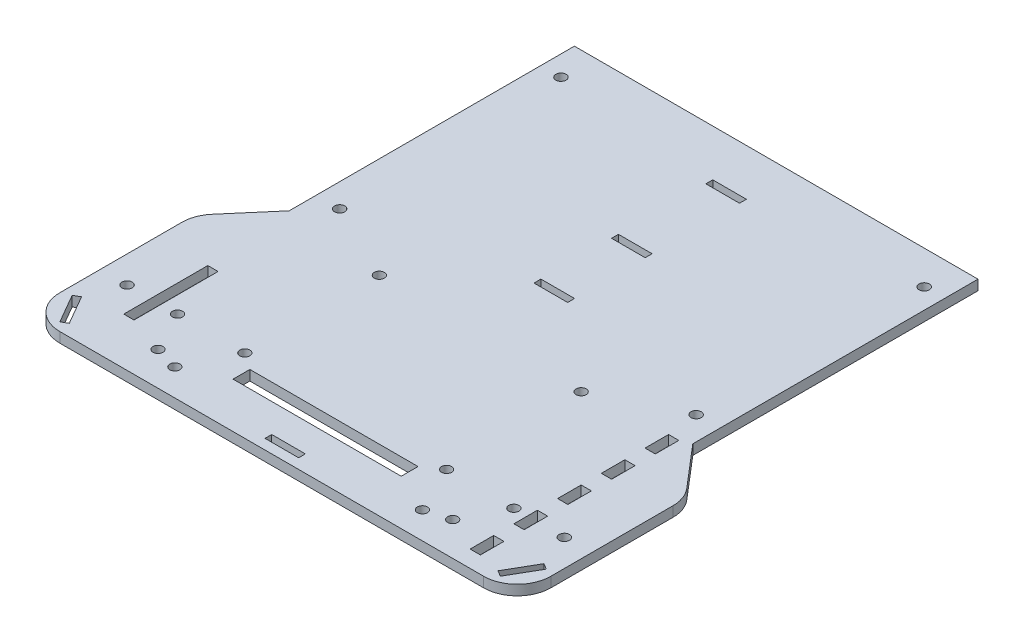
SolidWorks part; units mm, degrees
material "Perspex (TM) GS Acrylic Cast Sheet"
ref_plane "Front Plane" through (0, 0, 0) normal (0, 0, 1) x (1, 0, 0)
ref_plane "Top Plane" through (0, 0, 0) normal (0, 1, 0) x (1, 0, 0)
ref_plane "Right Plane" through (0, 0, 0) normal (1, 0, 0) x (0, 0, -1)
sketch "Sketch1" plane through (0, 0, 0) normal (0, 1, 0) x (1, 0, 0)
  line L0 (-73, -25) -> (-60, -9.8013)
  line L1 (60, -75) -> (-60, -75)
  line L2 (60, -9.8013) -> (60, 75)
  line L3 (60, 75) -> (-60, 75)
  line L4 (-60, -9.8013) -> (-60, 75)
  line L5 (60, -75) -> (-60, 75) construction
  line L6 (60, 75) -> (-60, -75) construction
  line L7 (0, 0) -> (0, -75) construction
  line L9 (-60, -75) -> (-73, -75)
  line L10 (-73, -25) -> (-73, -75)
  line L11 (60, -75) -> (73, -75)
  line L12 (73, -25) -> (73, -75)
  line L13 (73, -25) -> (60, -9.8013)
  point P0 (0, 0)
  dimension "D1" = 150
  dimension "D2" = 120
  dimension "D3" = 50
  dimension "D4" = 13
  dimension "D5" = 20
extrude "Boss-Extrude1" add sketch "Sketch1" along normal blind 3
sketch "Sketch2" plane through (0, 3, 0) normal (0, 1, 0) x (1, 0, 0)
  line L0 (0, 0) -> (0, 75) construction
  line L1 (60, 75) -> (-60, 75) construction
  line L2 (-60, 75) -> (-60, -9.8013) construction
  circle A0 centre (-53, -1.81) radius 1.525
  circle A1 centre (-54, 65) radius 1.525
  circle A2 centre (53, -1.81) radius 1.525
  circle A3 centre (54, 65) radius 1.525
  dimension "D1" = 10
  dimension "D2" = 3.05
  dimension "D3" = 6
  dimension "D4" = 3.05
  dimension "D5" = 7
  dimension "D6" = 66.81
extrude "Cut-Extrude1" cut sketch "Sketch2" against normal through all
sketch "Sketch3" plane through (0, 3, 0) normal (0, 1, 0) x (1, 0, 0)
  line L0 (-5, 33.09) -> (5, 33.09)
  line L1 (-5, 10.04) -> (5, 10.04)
  line L2 (-5, 10.04) -> (-5, 7.99)
  line L3 (-5, 7.99) -> (5, 7.99)
  line L4 (5, 10.04) -> (5, 7.99)
  line L5 (-5, 10.04) -> (5, 7.99) construction
  line L6 (-5, 7.99) -> (5, 10.04) construction
  line L7 (-5, 33.09) -> (-5, 31.04)
  line L8 (-5, 31.04) -> (5, 31.04)
  line L9 (5, 33.09) -> (5, 31.04)
  line L11 (-5, 61.14) -> (5, 61.14)
  line L12 (-5, 61.14) -> (-5, 59.09)
  line L13 (-5, 59.09) -> (5, 59.09)
  line L14 (-5, 56.14) -> (5, 56.14) [skipped]
  line L15 (-5, 56.14) -> (-5, 54.09) [skipped]
  line L16 (-5, 54.09) -> (5, 54.09) [skipped]
  line L17 (5, 56.14) -> (5, 54.09) [skipped]
  line L18 (5, 61.14) -> (5, 59.09)
  line L19 (-5, 61.14) -> (5, 59.09) construction
  line L20 (-5, 59.09) -> (5, 61.14) construction
  circle A0 centre (-53, -1.81) radius 1.525 construction
  point P0 (0, 9.015)
  point P8 (0, 60.115)
  dimension "D2" = 9.8
  dimension "D1" = 2.05
  dimension "D3" = 10
  dimension "D4" = 0
  dimension "D6" = 2.05
  dimension "D7" = 10
  dimension "D8" = 0
  dimension "D9" = 26
  dimension "D10" = 21
  dimension "D5" = 3
extrude "Cut-Extrude2" cut sketch "Sketch3" against normal through all
sketch "Sketch4" plane through (0, 3, 0) normal (0, 1, 0) x (1, 0, 0)
  line L0 (-73, -75) -> (73, -75) construction
  line L1 (-60, 75) -> (-60, -9.8013) construction
  line L2 (0, 0) -> (0, -75) construction
  line L4 (-73, -75) -> (73, -75) construction
  circle A1 centre (-50, -53) radius 1.5
  circle A2 centre (-43.8153, -65) radius 1.5
  circle A3 centre (43.8153, -65) radius 1.5
  circle A4 centre (50, -53) radius 1.5
  dimension "D1" = 3
  dimension "D2" = 3
  dimension "D4" = 10
  dimension "D5" = 13.5
  dimension "D6" = 10
  dimension "D3" = 22
extrude "Cut-Extrude3" cut sketch "Sketch4" against normal blind 3
sketch "Sketch5" plane through (0, 3, 0) normal (0, 1, 0) x (1, 0, 0)
  line L0 (0, 0) -> (0, -75) construction
  line L1 (-73, -75) -> (73, -75) construction
  line L2 (25, -61.5) -> (-25, -61.5)
  line L3 (25, -61.5) -> (25, -56.5)
  line L4 (25, -56.5) -> (-25, -56.5)
  line L5 (-25, -61.5) -> (-25, -56.5)
  line L6 (25, -61.5) -> (-25, -56.5) construction
  line L7 (-73, -75) -> (73, -75) construction
  line L8 (25, -56.5) -> (-25, -61.5) construction
  line L9 (-73, -25) -> (-73, -75) construction
  circle A0 centre (-36.8, -67) radius 1.5
  circle A1 centre (36.8, -67) radius 1.5
  circle A2 centre (-65, -53) radius 1.525
  circle A3 centre (65, -53) radius 1.525
  point P0 (0, -59)
  dimension "D3" = 3
  dimension "D4" = 5.5
  dimension "D5" = 8
  dimension "D7" = 3.05
  dimension "D9" = 8
  dimension "D1" = 5
  dimension "D2" = 50
  dimension "D6" = 36.8
  dimension "D8" = 22
extrude "Cut-Extrude4" cut sketch "Sketch5" against normal blind 3
sketch "Sketch6" plane through (0, 3, 0) normal (0, 1, 0) x (1, 0, 0)
  line L5 (25, -61.5) -> (25, -56.5) construction
  line L11 (-73, -75) -> (73, -75) construction
  line L12 (57.05, -50) -> (57.05, -57)
  line L24 (54, -63) -> (54, -70)
  line L25 (54, -63) -> (57.05, -63)
  line L26 (57.05, -63) -> (57.05, -70)
  line L27 (54, -70) -> (57.05, -70)
  line L28 (54, -50) -> (57.05, -50)
  line L29 (54, -50) -> (54, -57)
  line L30 (54, -57) -> (57.05, -57)
  line L31 (57.05, -37) -> (57.05, -44)
  line L32 (54, -37) -> (57.05, -37)
  line L33 (54, -37) -> (54, -44)
  line L34 (54, -44) -> (57.05, -44)
  line L35 (57.05, -24) -> (57.05, -31)
  line L36 (54, -24) -> (57.05, -24)
  line L37 (54, -24) -> (54, -31)
  line L38 (54, -31) -> (57.05, -31)
  line L39 (57.05, -11) -> (57.05, -18)
  line L40 (54, -11) -> (57.05, -11)
  line L41 (54, -11) -> (54, -18)
  line L42 (54, -18) -> (57.05, -18)
  dimension "D1" = 29
  dimension "D2" = 3.05
  dimension "D3" = 5
  dimension "D4" = 7
  dimension "D5" = 5
  dimension "D6" = 6
extrude "Cut-Extrude5" cut sketch "Sketch6" against normal blind 10
sketch "Sketch7" plane through (0, 3, 0) normal (0, 1, 0) x (1, 0, 0)
  line L0 (-73, -25) -> (-73, -75) construction
  line L1 (54, -40.5) -> (-47.7588, -40.5) construction
  line L2 (-73, -75) -> (73, -75) construction
  line L3 (5, -72) -> (-5, -72)
  line L8 (0, -75) -> (0, -22.2641) construction
  line L13 (5, -72) -> (5, -70)
  line L14 (5, -70) -> (-5, -70)
  line L15 (-5, -72) -> (-5, -70)
  line L20 (5, -72) -> (-5, -70) construction
  line L25 (5, -70) -> (-5, -72) construction
  line L27 (54, -37) -> (54, -44) construction
  line L28 (-58, -61) -> (-54.95, -61)
  line L29 (-58, -61) -> (-58, -36)
  line L30 (-58, -36) -> (-54.95, -36)
  line L31 (-54.95, -61) -> (-54.95, -36)
  line L32 (-58, -61) -> (-54.95, -36) construction
  line L33 (-58, -36) -> (-54.95, -61) construction
  point P10 (0, -71)
  point P18 (-56.475, -48.5)
  dimension "D2" = 2
  dimension "D3" = 25
  dimension "D7" = 3
  dimension "D10" = 15
  dimension "D8" = 3.05
  dimension "D4" = 10
  dimension "D9" = 14
extrude "Cut-Extrude6" cut sketch "Sketch7" against normal blind 10
fillet "Fillet3" radius 10 4 edges at (-73, 1.5, 25) (73, 1.5, 25) (73, 1.5, 75) (-73, 1.5, 75)
sketch "Sketch8" plane through (0, 3, 0) normal (0, 1, 0) x (1, 0, 0)
  line L5 (70.5, -63.8397) -> (65.5, -72.5)
  line L6 (65.5, -72.5) -> (63.7246, -71.475)
  line L8 (-63, -75) -> (63, -75) construction
  line L9 (0, -75) -> (0, -22.4512) construction
  line L14 (63.7246, -71.475) -> (68.7246, -62.8147)
  line L15 (68.7246, -62.8147) -> (70.5, -63.8397)
  line L17 (-68.7246, -62.8147) -> (-70.5, -63.8397)
  line L18 (-63.7246, -71.475) -> (-68.7246, -62.8147)
  line L19 (-65.5, -72.5) -> (-63.7246, -71.475)
  line L20 (-70.5, -63.8397) -> (-65.5, -72.5)
  line L21 (73, -65) -> (73, -28.6933) construction
  dimension "D1" = 2.05
  dimension "D2" = 10
  dimension "D3" = 60
  dimension "D4" = 2.5
  dimension "D5" = 2.5
extrude "Cut-Extrude7" cut sketch "Sketch8" against normal blind 10
sketch "Sketch9" plane through (0, 3, 0) normal (0, 1, 0) x (1, 0, 0)
  line L0 (0, 0) -> (0, -75) construction
  line L1 (-73, -33) -> (73, -33) construction
  line L2 (-63, -75) -> (63, -75) construction
  line L3 (-73, -28.6933) -> (-73, -65) construction
  line L4 (73, -65) -> (73, -28.6933) construction
  circle A0 centre (-30, -13) radius 1.5
  circle A2 centre (30, -13) radius 1.5
  circle A3 centre (30, -53) radius 1.5
  circle A4 centre (-30, -53) radius 1.5
  dimension "D2" = 3
  dimension "D1" = 20
  dimension "D3" = 22
  dimension "D4" = 30
extrude "Cut-Extrude8" cut sketch "Sketch9" against normal blind 3
